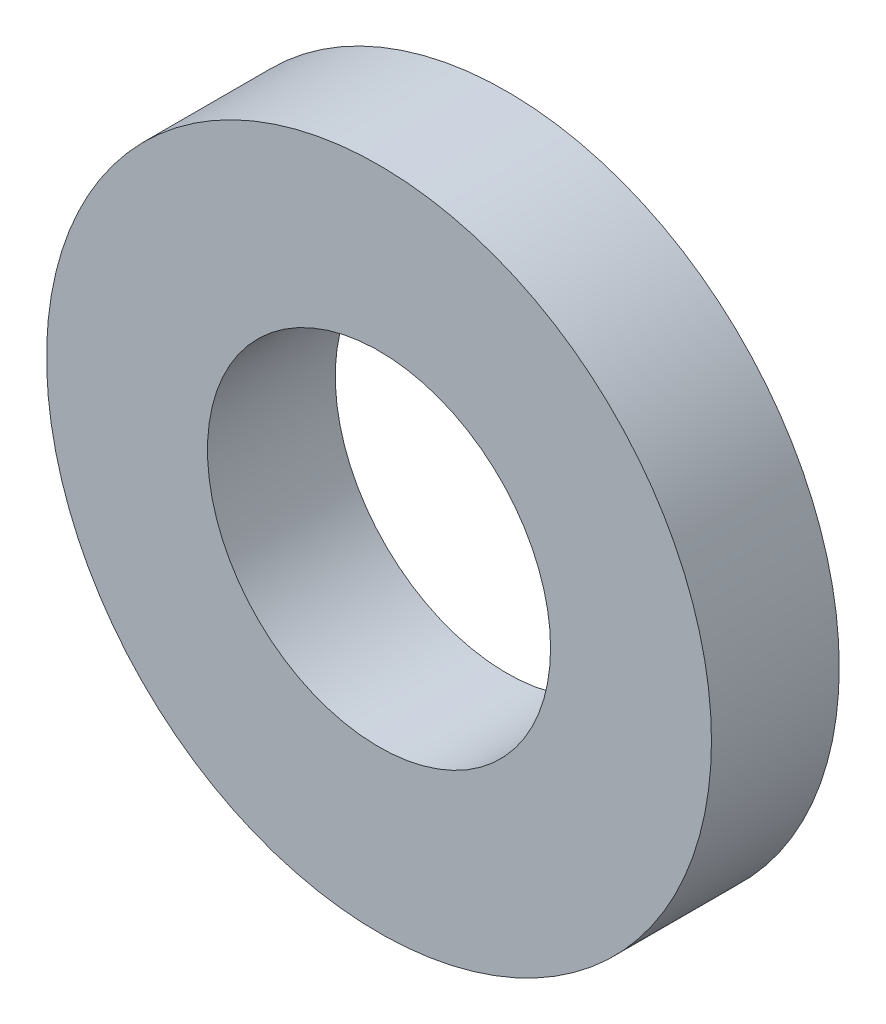
SolidWorks part; units mm, degrees
material "Rubber"
ref_plane "Front Plane" through (0, 0, 0) normal (0, 0, 1) x (1, 0, 0)
ref_plane "Top Plane" through (0, 0, 0) normal (0, 1, 0) x (1, 0, 0)
ref_plane "Right Plane" through (0, 0, 0) normal (1, 0, 0) x (0, 0, -1)
sketch "Sketch1" plane through (0, 0, 0) normal (0, 0, 1) x (1, 0, 0)
  circle A0 centre (0, 0) radius 3.683
  circle A1 centre (0, 0) radius 7.1374
  dimension "ID" = 7.366
  dimension "OD" = 14.2748
extrude "Extrude1" add sketch "Sketch1" against normal blind 2.7432
